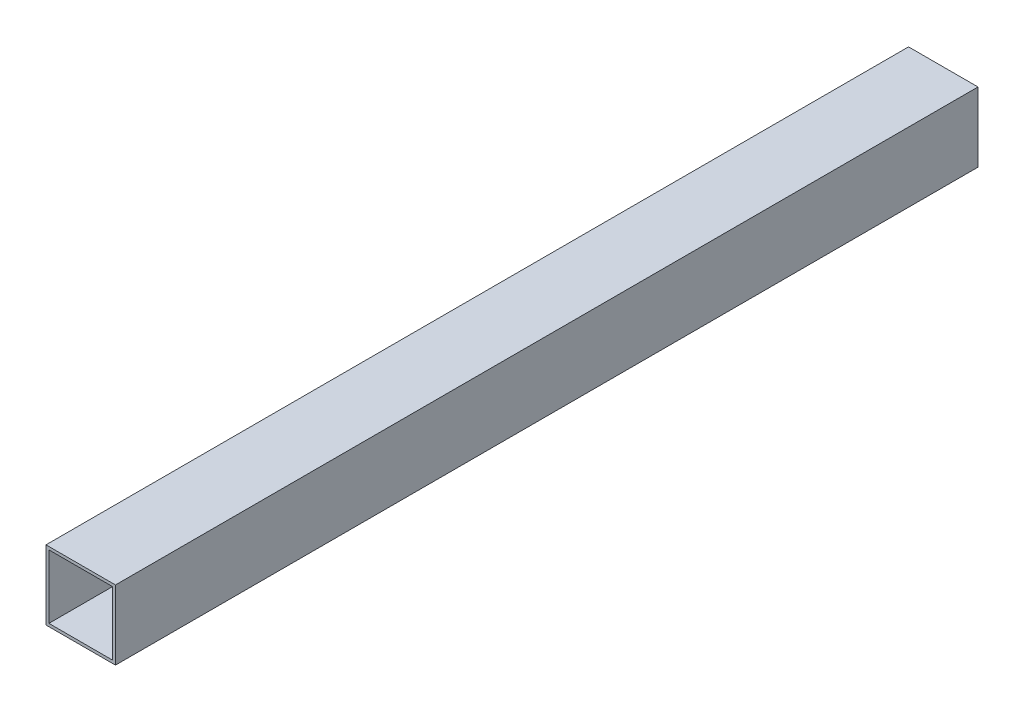
SolidWorks part; units mm, degrees
material "Custom Plastic"
ref_plane "Front Plane" through (0, 0, 0) normal (0, 0, 1) x (1, 0, 0)
ref_plane "Top Plane" through (0, 0, 0) normal (0, 1, 0) x (1, 0, 0)
ref_plane "Right Plane" through (0, 0, 0) normal (1, 0, 0) x (0, 0, -1)
sketch "Sketch2" plane through (0, 0, 0) normal (0, 0, 1) x (1, 0, 0)
  line L9 (-40.7297, 18.631) -> (35.4703, 18.631)
  line L10 (-40.7297, 18.631) -> (-40.7297, -57.569)
  line L11 (-40.7297, -57.569) -> (35.4703, -57.569)
  line L12 (35.4703, 18.631) -> (35.4703, -57.569)
extrude "Boss-Extrude1" add sketch "Sketch2" along normal blind 946.15 contours L10 L11 L12 L9
sketch "Sketch3" plane through (0, 0, 946.15) normal (0, 0, 1) x (1, 0, 0)
  line L0 (35.4703, 18.631) -> (35.4703, -57.569) construction
  line L1 (-40.7297, -57.569) -> (35.4703, -57.569) construction
  line L2 (-40.7297, 18.631) -> (-40.7297, -57.569) construction
  line L3 (-40.7297, 18.631) -> (35.4703, 18.631) construction
  line L4 (35.4703, 18.631) -> (35.4703, -57.569)
  line L5 (-40.7297, -57.569) -> (35.4703, -57.569)
  line L6 (-40.7297, 18.631) -> (-40.7297, -57.569)
  line L7 (-40.7297, 18.631) -> (35.4703, 18.631)
  line L9 (-37.5547, 15.456) -> (32.2953, 15.456)
  line L10 (-37.5547, 15.456) -> (-37.5547, -54.394)
  line L11 (-37.5547, -54.394) -> (32.2953, -54.394)
  line L12 (32.2953, 15.456) -> (32.2953, -54.394)
  dimension "D1" = 69.85
  dimension "D2" = 69.85
  dimension "D3" = 3.175
  dimension "D4" = 3.175
extrude "Cut-Extrude1" cut sketch "Sketch3" against normal blind 1098.55 contours L10 L11 L12 L9
sketch "Sketch4" plane through (-40.7297, 0, 0) normal (-1, 0, 0) x (0, 0, 1)
  circle A7 centre (838.2, -0.419) radius 4.318
  circle A8 centre (800.1, -0.419) radius 4.318
  circle A9 centre (838.2, -38.519) radius 4.318
  circle A10 centre (800.1, -38.519) radius 4.318
  circle A11 centre (298.45, -0.419) radius 4.318
  circle A12 centre (260.35, -0.419) radius 4.318
  circle A13 centre (260.35, -38.519) radius 4.318
  circle A14 centre (298.45, -38.519) radius 4.318
  circle A15 centre (530.225, -0.419) radius 4.318
  circle A16 centre (568.325, -0.419) radius 4.318
  circle A17 centre (568.325, -38.519) radius 4.318
  circle A18 centre (530.225, -38.519) radius 4.318
